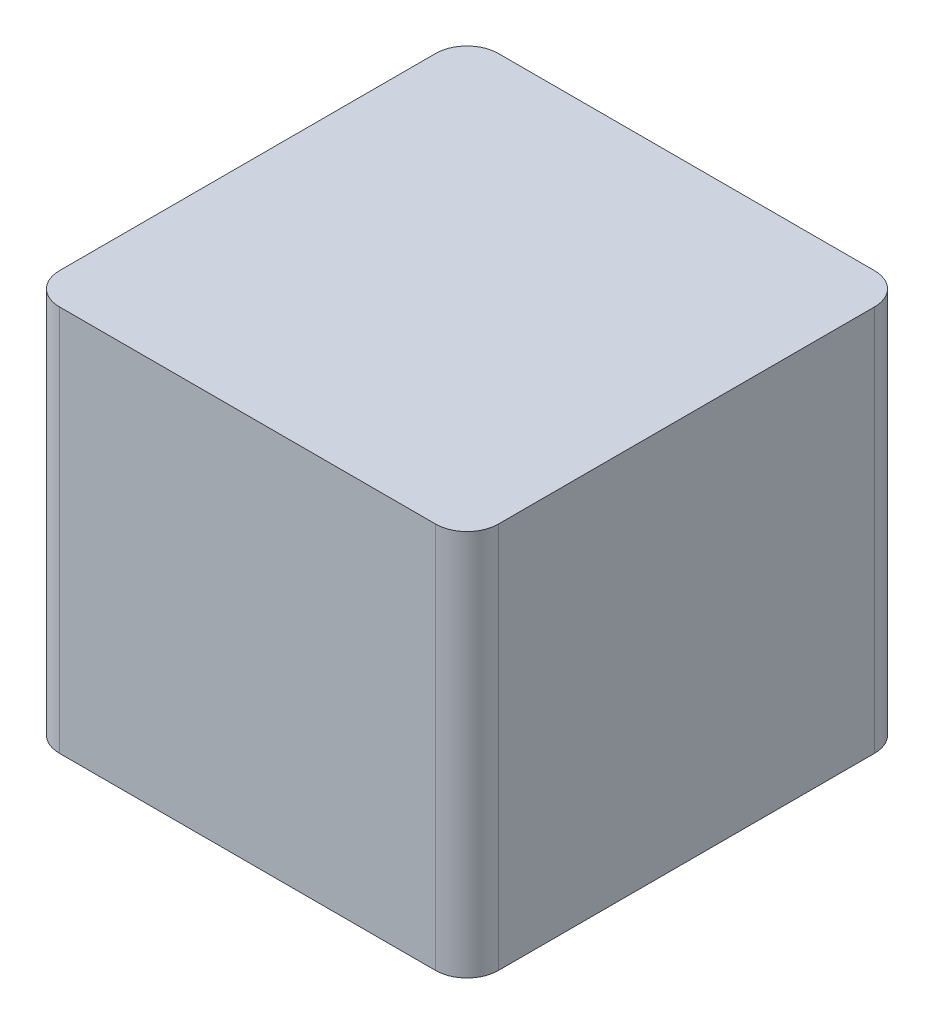
SolidWorks part; units mm, degrees
ref_plane "前视基准面" through (0, 0, 0) normal (0, 0, 1) x (1, 0, 0)
ref_plane "上视基准面" through (0, 0, 0) normal (0, 1, 0) x (1, 0, 0)
ref_plane "右视基准面" through (0, 0, 0) normal (1, 0, 0) x (0, 0, -1)
other "Configuration Table"
sketch "草图1" plane through (0, 0, 0) normal (0, 0, 1) x (1, 0, 0)
  line L0 (0, 0) -> (42, 0)
  line L1 (42, 0) -> (42, 37)
  line L2 (42, 37) -> (0, 37)
  line L3 (0, 37) -> (0, 0)
  dimension "width" = 42
  dimension "height" = 37
extrude "BlockExtrude" add sketch "草图1" along normal blind 42
fillet "Fillet" radius 3 4 edges at (0, 18.5, 0) (42, 18.5, 0) (0, 18.5, 42) (42, 18.5, 42)
